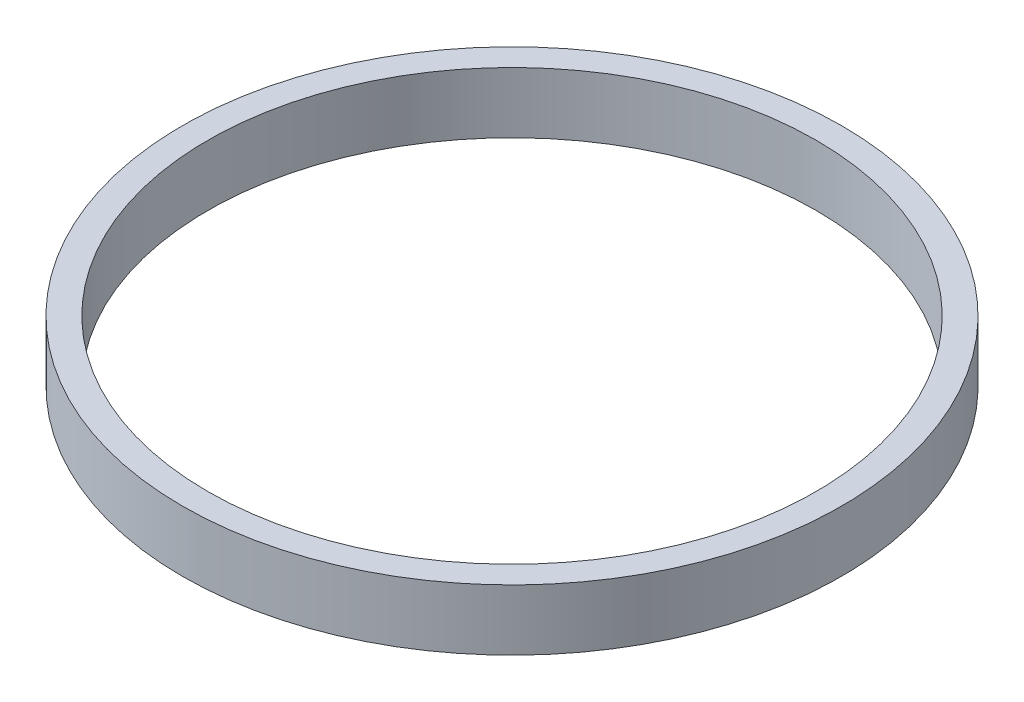
SolidWorks part; units mm, degrees
ref_plane "Front Plane" through (0, 0, 0) normal (0, 0, 1) x (1, 0, 0)
ref_plane "Top Plane" through (0, 0, 0) normal (0, 1, 0) x (1, 0, 0)
ref_plane "Right Plane" through (0, 0, 0) normal (1, 0, 0) x (0, 0, -1)
sketch "Sketch1" plane through (0, 0, 0) normal (0, 1, 0) x (1, 0, 0)
  circle A0 centre (0, 0) radius 32.5
  circle A1 centre (0, 0) radius 30
  dimension "D1" = 65
  dimension "D2" = 60
extrude "Boss-Extrude1" add sketch "Sketch1" along normal mid plane 6
